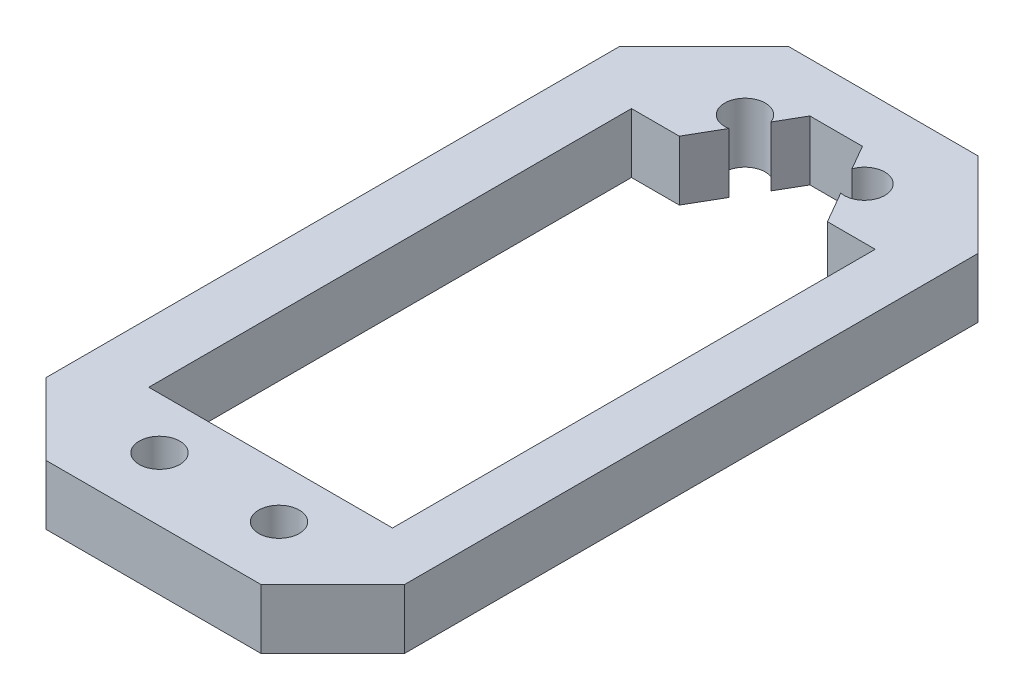
SolidWorks part; units mm, degrees
ref_plane "前视基准面" through (0, 0, 0) normal (0, 0, 1) x (1, 0, 0)
ref_plane "上视基准面" through (0, 0, 0) normal (0, 1, 0) x (1, 0, 0)
ref_plane "右视基准面" through (0, 0, 0) normal (1, 0, 0) x (0, 0, -1)
sketch "草图1" plane through (0, 0, 0) normal (0, 1, 0) x (1, 0, 0)
  line L0 (1434.4116, 1413.8632) -> (1434.4116, 1373.4632)
  line L1 (1434.4116, 1373.4632) -> (1414.0116, 1373.4632)
  line L2 (1414.0116, 1373.4632) -> (1414.0116, 1413.8632)
  line L3 (1439.0116, 1417.8632) -> (1439.0116, 1369.8632)
  line L4 (1433.0116, 1363.8632) -> (1415.0116, 1363.8632)
  line L5 (1409.0116, 1369.8632) -> (1409.0116, 1417.8632)
  line L6 (1439.0116, 1369.8632) -> (1433.0116, 1363.8632)
  line L7 (1415.0116, 1363.8632) -> (1409.0116, 1369.8632)
  line L8 (1414.0116, 1413.8632) -> (1418.0116, 1413.8632)
  line L9 (1418.0116, 1413.8632) -> (1419.5301, 1416.4933)
  line L10 (1420.817, 1418.7223) -> (1422.0116, 1420.7914)
  line L11 (1434.4116, 1413.8632) -> (1430.4116, 1413.8632)
  line L12 (1430.4116, 1413.8632) -> (1428.8931, 1416.4933)
  line L13 (1427.6062, 1418.7223) -> (1426.4116, 1420.7914)
  line L14 (1426.4116, 1420.7914) -> (1422.0116, 1420.7914)
  line L15 (1409.0116, 1417.8632) -> (1416.0827, 1424.9343)
  line L16 (1439.0116, 1417.8632) -> (1431.9405, 1424.9343)
  line L17 (1431.9405, 1424.9343) -> (1416.0827, 1424.9343)
  circle A0 centre (1429.2116, 1369.1632) radius 1.7
  circle A1 centre (1419.2116, 1369.1632) radius 1.7
  arc A2 (1428.8931, 1416.4933) -> (1427.6062, 1418.7223) centre (1429.2116, 1418.1632) ccw
  arc A3 (1420.817, 1418.7223) -> (1419.5301, 1416.4933) centre (1419.2116, 1418.1632) ccw
extrude "凸台-拉伸1" add sketch "草图1" along normal blind 5
